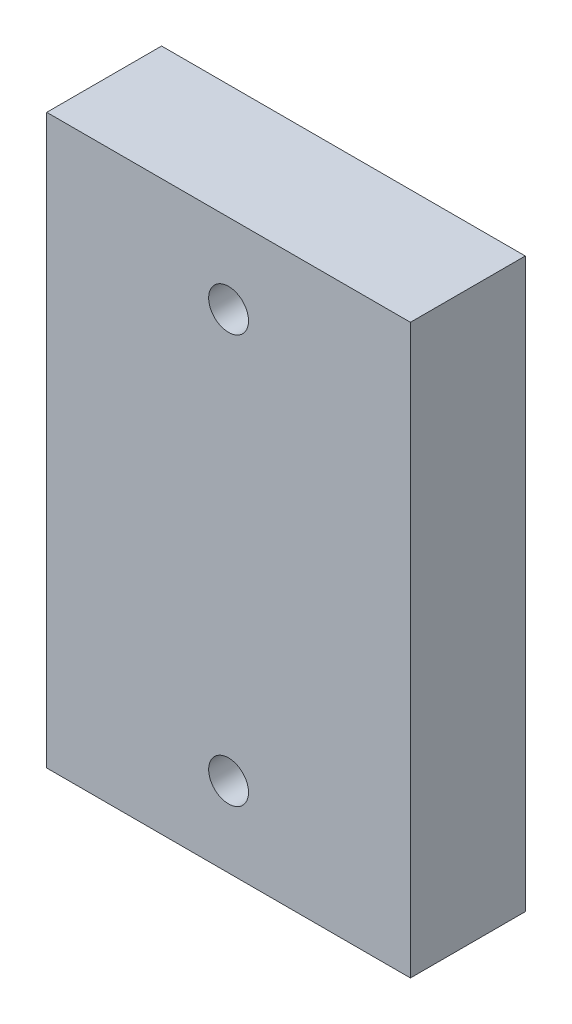
SolidWorks part; units mm, degrees
ref_plane "Front Plane" through (0, 0, 0) normal (0, 0, 1) x (1, 0, 0)
ref_plane "Top Plane" through (0, 0, 0) normal (0, 1, 0) x (1, 0, 0)
ref_plane "Right Plane" through (0, 0, 0) normal (1, 0, 0) x (0, 0, -1)
sketch "Sketch1" plane through (0, 0, 0) normal (0, 0, 1) x (1, 0, 0)
  line L1 (-103.0595, 39.1821) -> (-45.1475, 39.1821)
  line L2 (-103.0595, 39.1821) -> (-103.0595, -51.2419)
  line L3 (-103.0595, -51.2419) -> (-45.1475, -51.2419)
  line L4 (-45.1475, 39.1821) -> (-45.1475, -51.2419)
  dimension "D1" = 57.912
  dimension "D2" = 90.424
extrude "Boss-Extrude1" add sketch "Sketch1" along normal blind 18.288
sketch "Sketch2" plane through (0, 0, 18.288) normal (0, 0, 1) x (1, 0, 0)
  circle A0 centre (-74.1035, 26.4821) radius 3.175
  circle A1 centre (-74.1035, -38.5419) radius 3.175
extrude "Cut-Extrude2" cut sketch "Sketch2" against normal blind 25.4
